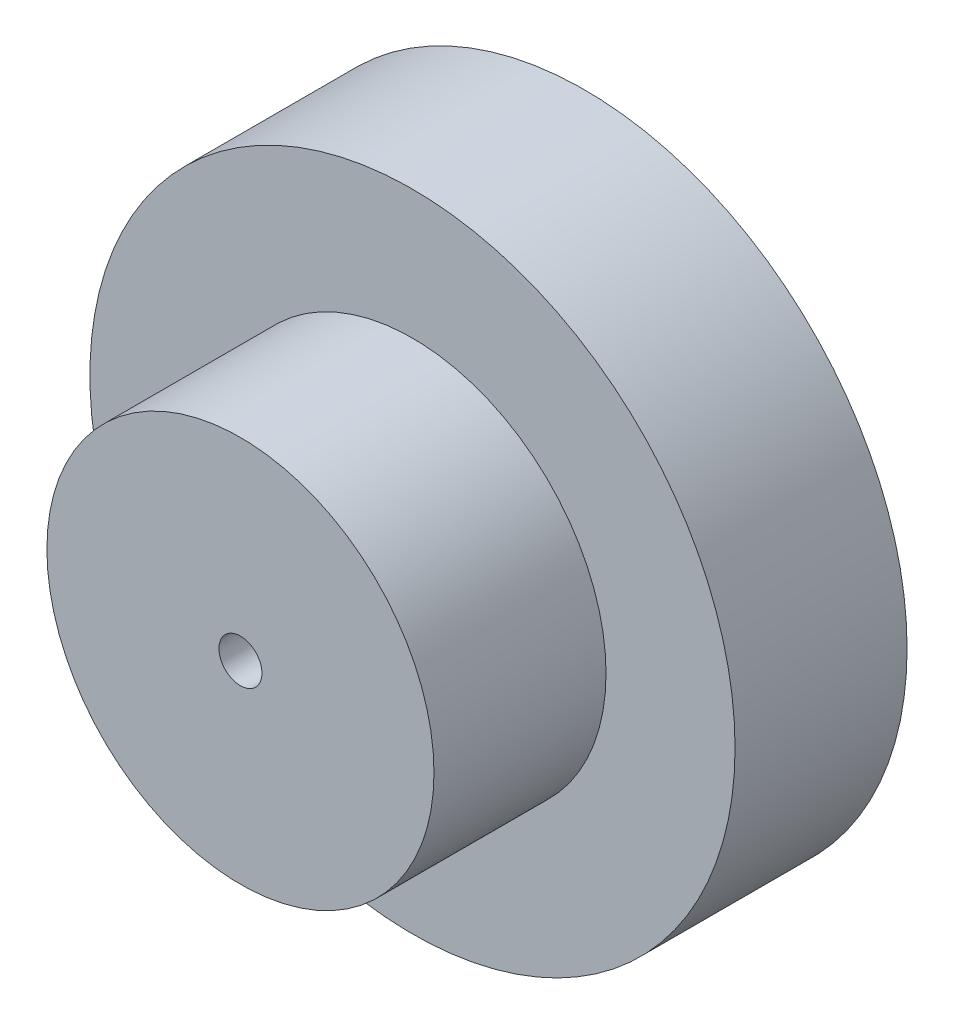
SolidWorks part; units mm, degrees
ref_plane "前视基准面" through (0, 0, 0) normal (0, 0, 1) x (1, 0, 0)
ref_plane "上视基准面" through (0, 0, 0) normal (0, 1, 0) x (1, 0, 0)
ref_plane "右视基准面" through (0, 0, 0) normal (1, 0, 0) x (0, 0, -1)
sketch "草图1" plane through (0, 0, 0) normal (0, 0, 1) x (1, 0, 0)
  circle A0 centre (0, 0) radius 4.5
  dimension "D1" = 9
extrude "凸台-拉伸1" add sketch "草图1" along normal blind 8
sketch "草图3" plane through (0, 0, 0) normal (0, 0, 1) x (1, 0, 0)
  circle A0 centre (0, 0) radius 7.5
  dimension "D1" = 15
extrude "凸台-拉伸2" add sketch "草图3" along normal blind 4
sketch "草图4" plane through (0, 0, 0) normal (0, 0, -1) x (-1, 0, 0)
  point P0 (0, 0)
hole_wizard "Ø1.0mm 暗销孔1" positions "草图5" profile "草图6" hole size "Ø1.0" standard "GB" end condition through all
sketch "草图5" plane through (0, 0, 0) normal (0, 0, -1) x (-1, 0, 0)
  point P0 (0, 0)
sketch "草图6" plane through (0, 0, 0) normal (1, 0, 0) x (0, 1, 0)
  line L0 (0, 0) -> (0, 8)
  line L1 (0, 8) -> (0.5, 8)
  line L2 (0.5, 8) -> (0.5, 2.5)
  line L3 (0.5, 2.5) -> (3, 0)
  line L5 (3, 0) -> (0, 0)
  line L6 (-0.5, 2.5) -> (-3, 0) construction
  line L11 (0, -6.35) -> (0, 107.95) construction
  dimension "通孔孔直径" = 1
  dimension "通孔孔深度" = 8
  dimension "近端锥形沉头孔直径" = 6
  dimension "近端锥形沉头孔角度" = 90
